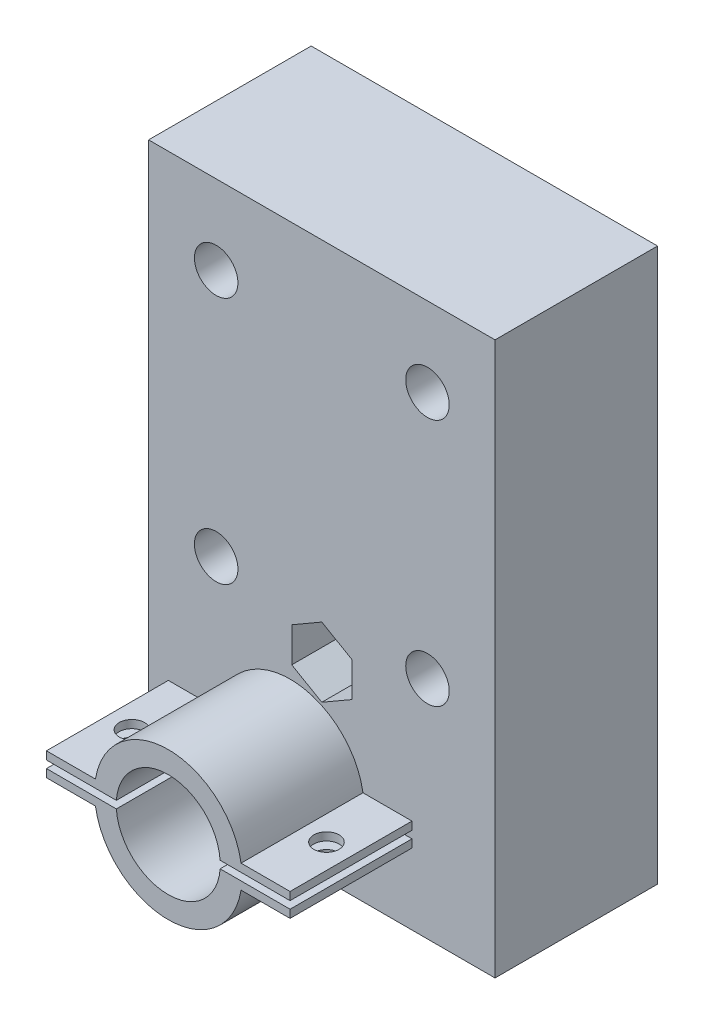
SolidWorks part; units mm, degrees
ref_plane "Front Plane" through (0, 0, 0) normal (0, 0, 1) x (1, 0, 0)
ref_plane "Top Plane" through (0, 0, 0) normal (0, 1, 0) x (1, 0, 0)
ref_plane "Right Plane" through (0, 0, 0) normal (1, 0, 0) x (0, 0, -1)
sketch "Sketch1" plane through (0, 0, 0) normal (0, 0, 1) x (1, 0, 0)
  line L0 (0, 25) -> (0, -25) construction
  line L1 (21.3115, 25) -> (-21.3115, 25)
  line L2 (21.3115, 25) -> (21.3115, -25)
  line L3 (21.3115, -25) -> (-21.3115, -25)
  line L4 (-21.3115, 25) -> (-21.3115, -25)
  line L5 (21.3115, 25) -> (-21.3115, -25) construction
  line L6 (21.3115, -25) -> (-21.3115, 25) construction
  line L7 (-21.3115, 0) -> (21.3115, 0) construction
  circle A0 centre (-13, -15.25) radius 2.677
  circle A1 centre (13, -15.25) radius 2.677
  circle A2 centre (13, 15.25) radius 2.677
  circle A3 centre (-13, 15.25) radius 2.677
  point P0 (0, 0)
  dimension "D1" = 30.5
  dimension "D2" = 26
  dimension "D3" = 50
extrude "Boss-Extrude1" add sketch "Sketch1" along normal blind 20
sketch "Sketch2" plane through (0, 0, 0) normal (0, 0, 1) x (1, 0, 0)
  circle A0 centre (0, 0) radius 8.73
  dimension "D1" = 17.46
extrude "Cut-Extrude2" cut sketch "Sketch2" along normal blind 7.94
sketch "Sketch3" plane through (0, 0, 0) normal (0, 0, -1) x (-1, 0, 0)
  circle A0 centre (0, -20) radius 2.2
  dimension "D1" = 4.4
  dimension "D2" = 20
extrude "Cut-Extrude3" cut sketch "Sketch3" against normal blind 10
sketch "Sketch5" plane through (0, 0, 0) normal (0, 0, -1) x (-1, 0, 0)
  line L1 (0, -15.7276) -> (-3.7, -17.8638)
  line L2 (-3.7, -17.8638) -> (-3.7, -22.1362)
  line L3 (-3.7, -22.1362) -> (0, -24.2724)
  line L4 (0, -24.2724) -> (3.7, -22.1362)
  line L5 (3.7, -22.1362) -> (3.7, -17.8638)
  line L6 (3.7, -17.8638) -> (0, -15.7276)
  circle A0 centre (0, -20) radius 3.7 construction
  dimension "D1" = 3.7
extrude "Cut-Extrude4" cut sketch "Sketch5" against normal through all from offset 7 offset against normal yes
sketch "Sketch6" plane through (0, 0, 0) normal (0, 0, -1) x (-1, 0, 0)
  circle A1 centre (3.8969, -32.824) radius 6.4
sketch "Sketch7" plane through (0, -25, 0) normal (0, -1, 0) x (1, 0, 0)
  line L1 (-21.3115, 20) -> (21.3115, 20)
  line L2 (-21.3115, 20) -> (-21.3115, 0)
  line L3 (-21.3115, 0) -> (21.3115, 0)
  line L4 (21.3115, 20) -> (21.3115, 0)
extrude "Boss-Extrude2" add sketch "Sketch7" along normal blind 18
extrude "Cut-Extrude5" cut sketch "Sketch6" against normal through all contours A1
sketch "Sketch8" plane through (0, 0, 20) normal (0, 0, 1) x (1, 0, 0)
  line L8 (2.487, -32.3693) -> (10.2737, -32.3693)
  line L10 (-18.8855, -31.924) -> (-18.8855, -32.3693)
  line L12 (11.0918, -31.924) -> (11.0918, -32.3693)
  line L13 (10.2737, -32.3693) -> (11.0918, -32.3693)
  line L15 (-18.0674, -32.3693) -> (-10.2807, -32.3693)
  line L17 (-18.0674, -33.2788) -> (-10.2807, -33.2788)
  line L19 (11.0918, -33.2788) -> (10.2737, -33.2788)
  line L20 (11.0918, -33.2788) -> (11.0918, -33.724)
  line L23 (-18.0674, -32.3693) -> (-18.8855, -32.3693)
  line L25 (-18.8855, -33.2788) -> (-18.0674, -33.2788)
  line L26 (-18.8855, -33.2788) -> (-18.8855, -33.724)
  line L27 (2.487, -33.2788) -> (10.2737, -33.2788)
  line L28 (5.0615, -34.2605) -> (11.0918, -34.2605)
  line L29 (-18.8855, -31.3876) -> (-12.8552, -31.3876)
  line L30 (-18.8855, -31.3876) -> (-18.8855, -32.3693)
  line L31 (-18.8855, -34.2605) -> (-12.8552, -34.2605)
  line L32 (11.0918, -31.3876) -> (11.0918, -32.3693)
  line L33 (-18.8855, -33.2788) -> (-18.8855, -34.2605)
  line L34 (5.0615, -31.3876) -> (11.0918, -31.3876)
  line L35 (11.0918, -33.2788) -> (11.0918, -34.2605)
  arc A0 (4.9456, -30.7927) -> (-12.7395, -30.7937) centre (-3.8969, -32.824) ccw
  arc A3 (-12.8552, -34.2605) -> (5.0615, -34.2605) centre (-3.8969, -32.824) ccw
  arc A7 (-12.8552, -34.2605) -> (5.0615, -34.2605) centre (-3.8969, -32.824) ccw
  arc A9 (5.0615, -31.3876) -> (-12.8552, -31.3876) centre (-3.8969, -32.824) ccw
  arc A11 (-10.2807, -33.2788) -> (2.487, -33.2788) centre (-3.8969, -32.824) ccw
  arc A12 (2.487, -32.3693) -> (-10.2807, -32.3693) centre (-3.8969, -32.824) ccw
  point P27 (11.0918, -34.2605)
  dimension "D2" = 1.8
extrude "Boss-Extrude5" add sketch "Sketch8" along normal blind 15
sketch "Sketch10" plane through (0, -43, 0) normal (0, -1, 0) x (1, 0, 0)
  line L0 (21.3115, 20) -> (-21.3115, 20) construction
  line L2 (-18.8855, 35) -> (-18.8855, 20) construction
  line L3 (11.0918, 35) -> (11.0918, 20) construction
  circle A0 centre (-15.8705, 27.5) radius 1.55
  circle A1 centre (8.0718, 27.5) radius 1.55
  dimension "D1" = 7.5
  dimension "D3" = 3.02
  dimension "D2" = 3.015
extrude "Cut-Extrude8" cut sketch "Sketch10" against normal through all
